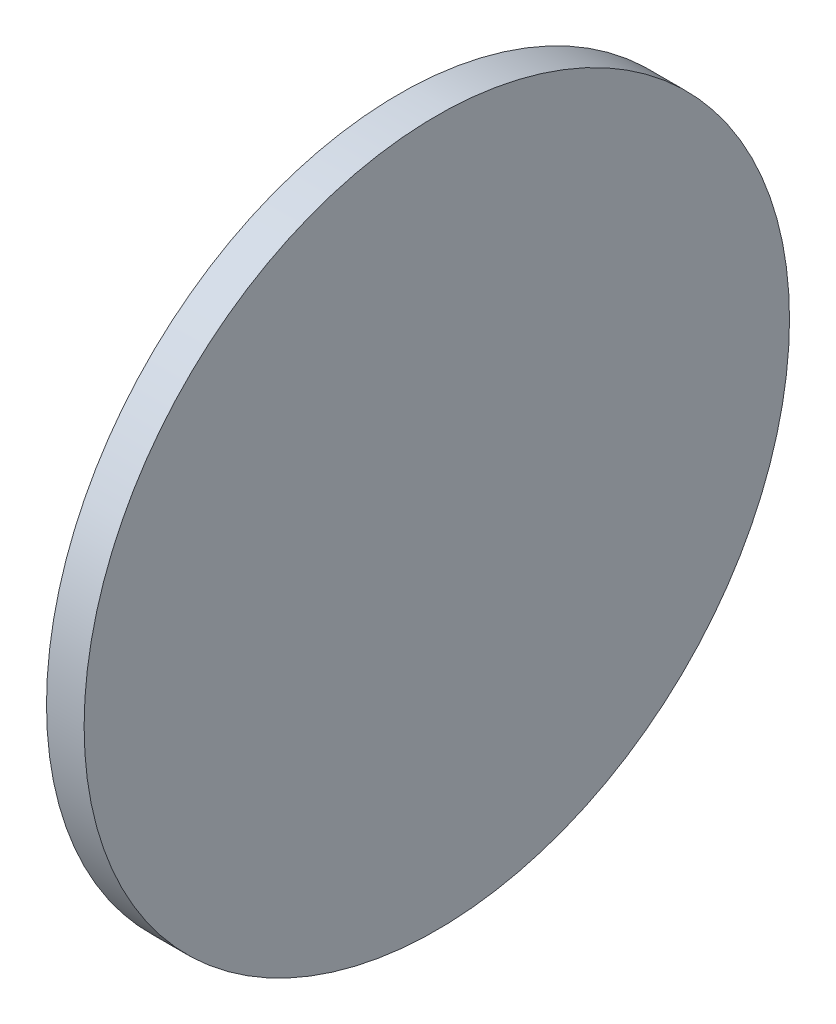
SolidWorks part; units mm, degrees
material "普通碳钢"
ref_plane "前视" through (0, 0, 0) normal (0, 0, 1) x (1, 0, 0)
ref_plane "上视" through (0, 0, 0) normal (0, 1, 0) x (1, 0, 0)
ref_plane "右视" through (0, 0, 0) normal (1, 0, 0) x (0, 0, -1)
sketch "草图1" plane through (0, 0, 0) normal (1, 0, 0) x (0, 0, -1)
  line L0 (0, 0) -> (0, 160)
  line L1 (0, 0) -> (120, 0)
  line L2 (120, 0) -> (120, 160)
  line L3 (60, 280) -> (60, 0) construction
  line L4 (39, 81) -> (39, 59) construction
  line L5 (40.5, 81) -> (40.5, 59)
  line L6 (37.5, 81) -> (37.5, 59)
  line L7 (81, 81) -> (81, 59) construction
  line L8 (79.5, 81) -> (79.5, 59)
  line L9 (82.5, 81) -> (82.5, 59)
  line L10 (60, 205) -> (6.967, 258.033) construction
  line L11 (60, 205) -> (113.033, 258.033) construction
  line L12 (-15, 205) -> (135, 205) construction
  line L13 (115, 5) -> (115, 161.6987) construction
  line L14 (5, 5) -> (115, 5) construction
  line L15 (5, 5) -> (5, 161.6987) construction
  arc A0 (0, 160) -> (120, 160) centre (60, 205) cw
  circle A1 centre (60, 205) radius 12.5
  circle A2 centre (25, 170) radius 7 construction
  circle A3 centre (95, 170) radius 7 construction
  circle A4 centre (25, 177) radius 1.75
  circle A5 centre (32, 170) radius 1.75
  circle A6 centre (25, 163) radius 1.75
  circle A7 centre (18, 170) radius 1.75
  circle A8 centre (95, 177) radius 1.75
  circle A9 centre (102, 170) radius 1.75
  circle A10 centre (95, 163) radius 1.75
  circle A11 centre (88, 170) radius 1.75
  circle A12 centre (39, 140) radius 1.75
  circle A13 centre (81, 140) radius 1.75
  arc A14 (40.5, 81) -> (37.5, 81) centre (39, 81) ccw
  arc A15 (37.5, 59) -> (40.5, 59) centre (39, 59) ccw
  arc A16 (79.5, 81) -> (82.5, 81) centre (81, 81) cw
  arc A17 (82.5, 59) -> (79.5, 59) centre (81, 59) cw
  circle A18 centre (60, 275) radius 1.75
  circle A19 centre (-10, 205) radius 1.75
  circle A20 centre (130, 205) radius 1.75
  circle A21 centre (10.5025, 254.4975) radius 1.75
  circle A22 centre (109.4975, 254.4975) radius 1.75
  arc A23 (5, 161.6987) -> (115, 161.6987) centre (60, 205) cw construction
  circle A24 centre (5, 5) radius 1.75
  circle A25 centre (115, 5) radius 1.75
  circle A26 centre (5, 120) radius 1.75
  circle A27 centre (115, 120) radius 1.75
  point P35 (39, 70)
  point P42 (81, 70)
  dimension "D2" = 75
  dimension "D4" = 25
  dimension "D5" = 14
  dimension "D7" = 3.5
  dimension "D8" = 170
  dimension "D9" = 3.5
  dimension "D14" = 3.5
  dimension "D15" = 115
  dimension "D16" = 140
  dimension "D17" = 25
  dimension "D18" = 1.5
  dimension "D1" = 120
  dimension "D3" = 280
  dimension "D6" = 70
  dimension "D10" = 42
  dimension "D11" = 45
  dimension "D12" = 90
  dimension "D19" = 70
  dimension "D13" = 5
extrude "凸台-拉伸1" add sketch "草图1" along normal blind 5
fillet "圆角1" radius 5 4 edges at (2.5, 160, 0) (2.5, 160, -120) (2.5, 0, -120) (2.5, 0, 0)
sketch "草图2" plane through (5, 0, 0) normal (1, 0, 0) x (0, 0, -1)
  line L0 (120, 5) -> (120, 158.3631) construction
  line L1 (44, 101) -> (60, 101) construction
  line L2 (44, 101) -> (44, 65) construction
  line L3 (44, 65) -> (60, 65) construction
  line L4 (60, 101) -> (60, 65) construction
  line L5 (5, 0) -> (115, 0) construction
  circle A1 centre (60, 101) radius 1.1
  circle A2 centre (60, 65) radius 1.1
  circle A3 centre (44, 65) radius 1.1
  circle A4 centre (44, 101) radius 1.1
  dimension "D4" = 2.2
  dimension "D1" = 36
  dimension "D2" = 16
  dimension "D3" = 65
  dimension "D5" = 60
sketch "草图3" plane through (0, 0, 0) normal (-1, 0, 0) x (0, 0, 1)
  line L0 (-20, 48.5) -> (-30, 48.5) construction
  line L1 (-20, 46.75) -> (-30, 46.75)
  line L2 (-20, 50.25) -> (-30, 50.25)
  line L3 (-90, 48.5) -> (-100, 48.5) construction
  line L4 (-90, 46.75) -> (-100, 46.75)
  line L5 (-90, 50.25) -> (-100, 50.25)
  line L6 (-20, 10) -> (-30, 10) construction
  line L7 (-20, 8.25) -> (-30, 8.25)
  line L8 (-20, 11.75) -> (-30, 11.75)
  line L9 (-90, 10) -> (-100, 10) construction
  line L10 (-90, 8.25) -> (-100, 8.25)
  line L11 (-90, 11.75) -> (-100, 11.75)
  line L12 (-60, 0) -> (-60, 280) construction
  line L13 (-25, 48.5) -> (-95, 48.5) construction
  line L14 (-25, 48.5) -> (-25, 10) construction
  line L15 (-25, 10) -> (-95, 10) construction
  line L16 (-95, 48.5) -> (-95, 10) construction
  line L17 (-5, 0) -> (-115, 0) construction
  circle A0 centre (-45.8181, 127.4583) radius 1.1
  circle A1 centre (-61.8181, 127.4583) radius 1.1
  circle A2 centre (-45.8181, 91.4583) radius 1.1
  circle A3 centre (-61.8181, 91.4583) radius 1.1
  arc A4 (-20, 46.75) -> (-20, 50.25) centre (-20, 48.5) ccw
  arc A5 (-30, 50.25) -> (-30, 46.75) centre (-30, 48.5) ccw
  arc A6 (-90, 46.75) -> (-90, 50.25) centre (-90, 48.5) ccw
  arc A7 (-100, 50.25) -> (-100, 46.75) centre (-100, 48.5) ccw
  arc A8 (-20, 8.25) -> (-20, 11.75) centre (-20, 10) ccw
  arc A9 (-30, 11.75) -> (-30, 8.25) centre (-30, 10) ccw
  arc A10 (-90, 8.25) -> (-90, 11.75) centre (-90, 10) ccw
  arc A11 (-100, 11.75) -> (-100, 8.25) centre (-100, 10) ccw
  arc A12 (0.9375, 161.2779) -> (-120.9375, 161.2779) centre (-60, 205) ccw construction
  point P16 (-25, 48.5)
  point P22 (-95, 48.5)
  point P29 (-25, 10)
  point P36 (-95, 10)
  dimension "D1" = 2.2
  dimension "D2" = 2.2
  dimension "D3" = 3.5
  dimension "D4" = 10
  dimension "D5" = 35
  dimension "D6" = 70
  dimension "D7" = 10
extrude "切除-拉伸2" cut sketch "草图3" against normal blind 10
sketch "草图4" plane through (0, 0, 0) normal (-1, 0, 0) x (0, 0, 1)
  line L0 (-60, 0) -> (-60, 280) construction
  line L1 (-5, 0) -> (-115, 0) construction
  line L2 (-81, 140) -> (-39, 140) construction
  circle A0 centre (-16.1189, 88.7406) radius 1.5
  circle A1 centre (-16.1189, 64.2406) radius 1.5
  circle A2 centre (-94, 140) radius 1.5
  circle A3 centre (-26, 140) radius 1.5
  arc A4 (0.9375, 161.2779) -> (-120.9375, 161.2779) centre (-60, 205) ccw construction
  circle A5 centre (-94, 82) radius 1.5
  circle A6 centre (-26, 82) radius 1.5
  dimension "D1" = 3
  dimension "D2" = 3
  dimension "D3" = 3
  dimension "D5" = 58
  dimension "D4" = 68
extrude "切除-拉伸3" cut sketch "草图4" against normal blind 10
sketch "Sketch1" plane through (0, 0, 0) normal (-1, 0, 0) x (0, 0, 1)
  line L0 (0.9375, 161.2779) -> (0.9375, -17.1775)
  line L1 (0.9375, -17.1775) -> (-120, -17.1775)
  line L2 (-120, -17.1775) -> (-120.9375, 161.2779)
  arc A0 (-120.9375, 161.2779) -> (0.9375, 161.2779) centre (-60, 205) ccw
extrude "Extrude1" cut sketch "Sketch1" against normal through all
sketch "Sketch2" plane through (5, 0, 0) normal (1, 0, 0) x (0, 0, -1)
  circle A1 centre (60, 205) radius 75
  circle A2 centre (60, 205) radius 75
  dimension "D1" = 0
extrude "Extrude2" add sketch "Sketch2" along normal blind 3
